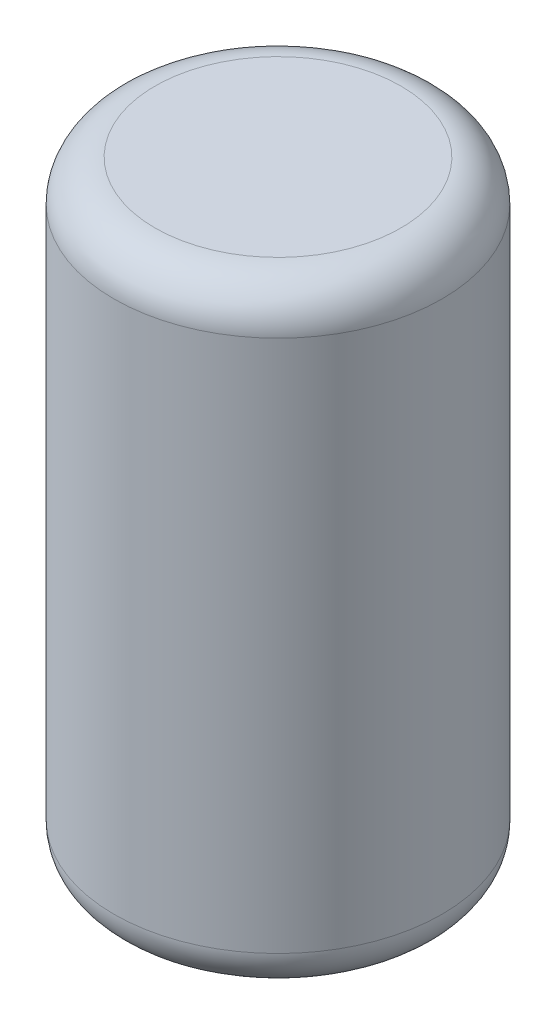
SolidWorks part; units mm, degrees
ref_plane "Front Plane" through (0, 0, 0) normal (0, 0, 1) x (1, 0, 0)
ref_plane "Top Plane" through (0, 0, 0) normal (0, 1, 0) x (1, 0, 0)
ref_plane "Right Plane" through (0, 0, 0) normal (1, 0, 0) x (0, 0, -1)
sketch "Sketch1" plane through (0, 0, 0) normal (0, 1, 0) x (1, 0, 0)
  circle A0 centre (0, 0) radius 4
  dimension "D1" = 8
extrude "Boss-Extrude1" add sketch "Sketch1" along normal blind 15
fillet "Fillet1" radius 1 2 edges at (0, 0, 4) (0, 15, 4)
scale "Scale1" scale about centroid uniform scaling yes scale factor 0.7
